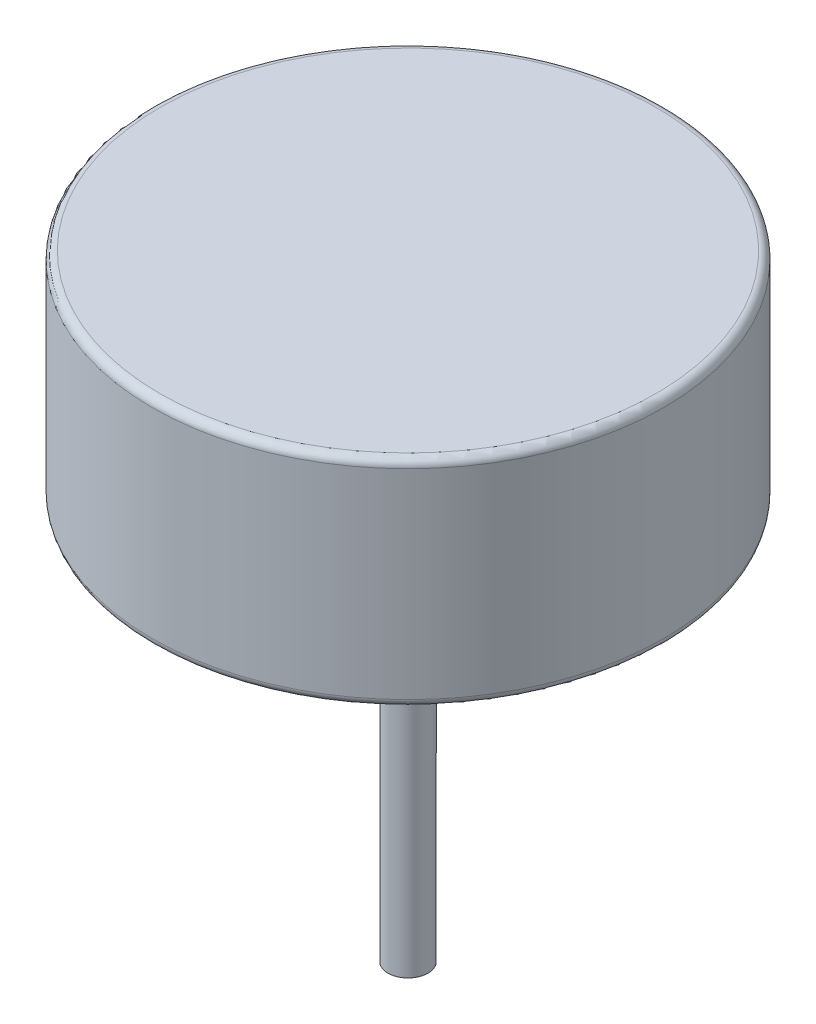
SolidWorks part; units mm, degrees
ref_plane "Front Plane" through (0, 0, 0) normal (0, 0, 1) x (1, 0, 0)
ref_plane "Top Plane" through (0, 0, 0) normal (0, 1, 0) x (1, 0, 0)
ref_plane "Right Plane" through (0, 0, 0) normal (1, 0, 0) x (0, 0, -1)
sketch "Sketch1" plane through (0, 0, 0) normal (0, 1, 0) x (1, 0, 0)
  circle A0 centre (0, 0) radius 32
  dimension "D1" = 64
extrude "Boss-Extrude1" add sketch "Sketch1" along normal mid plane 27
fillet "Fillet1" radius 1 1 edges at (0, -13.5, 32)
fillet "Fillet2" radius 1 1 edges at (0, 13.5, 32)
sketch "Sketch2" plane through (0, -13.5, 0) normal (0, -1, 0) x (-1, 0, 0)
  circle A0 centre (0, 0) radius 2.5
  dimension "D1" = 5
extrude "Boss-Extrude2" add sketch "Sketch2" along normal blind 50
sketch "Sketch3" plane through (0, -63.5, 0) normal (0, -1, 0) x (-1, 0, 0)
  line L0 (2.5, 0) -> (0, 0) construction
  line L1 (0, 0) -> (-2.5, 0) construction
  line L2 (0, -2.5) -> (0, 2.5) construction
  circle A0 centre (0, 0) radius 2.5 construction
  circle A1 centre (0, 0) radius 2.5 construction
